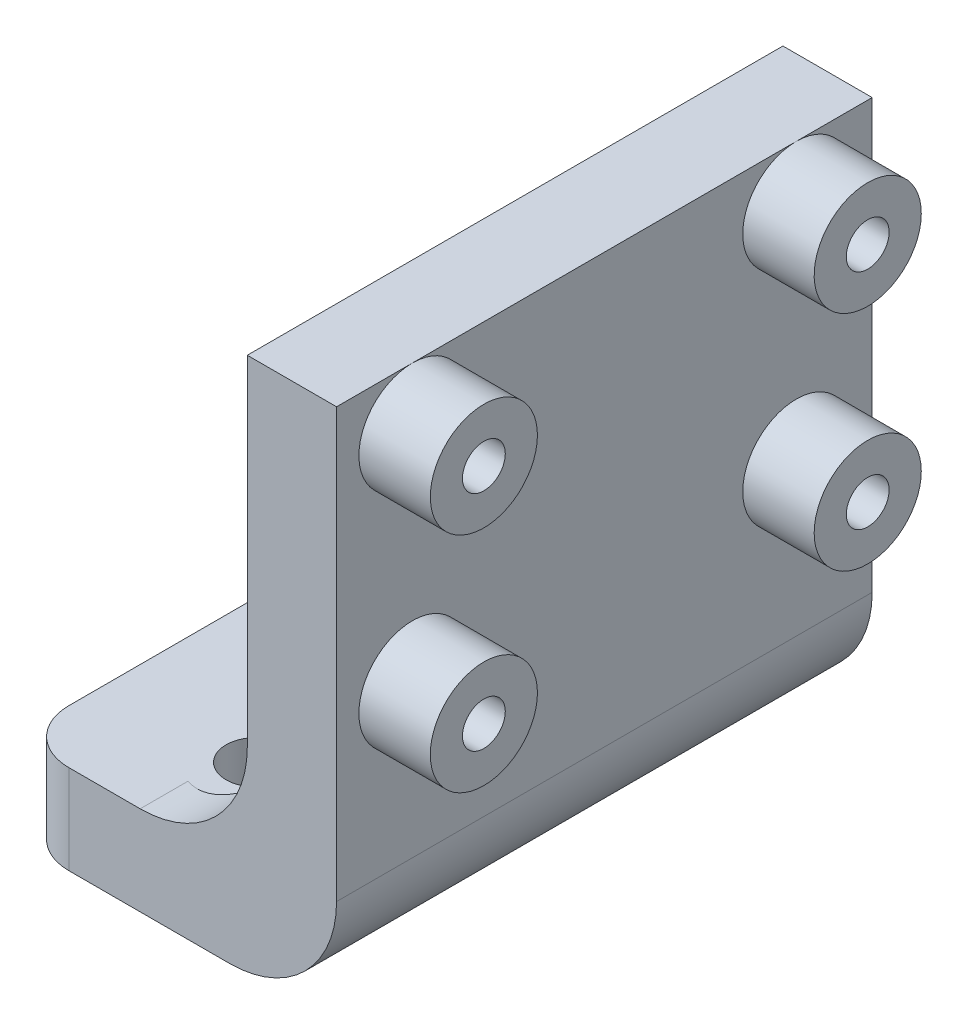
SolidWorks part; units mm, degrees
ref_plane "Front Plane" through (0, 0, 0) normal (0, 0, 1) x (1, 0, 0)
ref_plane "Top Plane" through (0, 0, 0) normal (0, 1, 0) x (1, 0, 0)
ref_plane "Right Plane" through (0, 0, 0) normal (1, 0, 0) x (0, 0, -1)
sketch "Sketch1" plane through (0, 0, 0) normal (0, 1, 0) x (1, 0, 0)
  line L1 (0, 0) -> (18, 0)
  line L2 (0, 0) -> (0, 30)
  line L3 (0, 30) -> (18, 30)
  line L4 (18, 0) -> (18, 30)
  dimension "D1" = 30
  dimension "D2" = 18
extrude "Boss-Extrude1" add sketch "Sketch1" along normal blind 5
sketch "Sketch2" plane through (18, 0, 0) normal (1, 0, 0) x (0, 0, -1)
  line L1 (0, 0) -> (30, 0)
  line L2 (0, 0) -> (0, 30)
  line L3 (0, 30) -> (30, 30)
  line L4 (30, 0) -> (30, 30)
  dimension "D1" = 30
  dimension "D2" = 30
extrude "Boss-Extrude2" add sketch "Sketch2" against normal blind 5
sketch "Sketch3" plane through (18, 0, 0) normal (1, 0, 0) x (0, 0, -1)
  line L0 (15, 30) -> (15, 10.1777) construction
  line L1 (30, 30) -> (0, 30) construction
  line L2 (15, 20.75) -> (28.8198, 20.75) construction
  circle A0 centre (4.25, 27) radius 1.2
  circle A1 centre (25.75, 27) radius 1.2
  circle A2 centre (25.75, 14.5) radius 1.2
  circle A3 centre (4.25, 14.5) radius 1.2
  dimension "D1" = 2.4
  dimension "D2" = 2.4
  dimension "D3" = 21.5
  dimension "D4" = 3
  dimension "D5" = 12.5
extrude "Cut-Extrude1" cut sketch "Sketch3" against normal blind 5
fillet "Fillet1" radius 6 2 edges at (13, 5, -15) (18, 0, -15)
sketch "Sketch4" plane through (18, 0, 0) normal (1, 0, 0) x (0, 0, -1)
  circle A0 centre (25.75, 27) radius 1.2 construction
  circle A1 centre (25.75, 14.5) radius 1.2 construction
  circle A2 centre (4.25, 14.5) radius 1.2 construction
  circle A3 centre (4.25, 27) radius 1.2 construction
  circle A4 centre (25.75, 27) radius 1.2
  circle A5 centre (25.75, 14.5) radius 1.2
  circle A6 centre (4.25, 14.5) radius 1.2
  circle A7 centre (4.25, 27) radius 1.2
  circle A8 centre (4.25, 27) radius 3
  circle A9 centre (25.75, 27) radius 3
  circle A10 centre (4.25, 14.5) radius 3
  circle A11 centre (25.75, 14.5) radius 3
  dimension "D1" = 6
  dimension "D2" = 6
  dimension "D3" = 6
  dimension "D4" = 6
extrude "Boss-Extrude3" add sketch "Sketch4" along normal blind 4
sketch "Sketch5" plane through (0, 0, 0) normal (0, -1, 0) x (1, 0, 0)
  circle A1 centre (8, -25.5101) radius 2.2 construction
  circle A2 centre (8, -5.5101) radius 2.2 construction
  circle A3 centre (8, -25.5101) radius 2.2 construction
  circle A4 centre (8, -5.5101) radius 2.2 construction
  circle A5 centre (8, -5.5101) radius 1.7
  circle A6 centre (8, -25.5101) radius 1.7
  dimension "D1" = 3.4
  dimension "D2" = 3.4
extrude "Cut-Extrude2" cut sketch "Sketch5" against normal blind 24
sketch "Sketch6" plane through (0, 5, 0) normal (0, 1, 0) x (1, 0, 0)
  circle A0 centre (8, 25.5101) radius 1.7 construction
  circle A1 centre (8, 5.5101) radius 1.7 construction
  circle A2 centre (8, 25.5101) radius 1.7 construction
  circle A3 centre (8, 5.5101) radius 1.7 construction
  circle A4 centre (8, 25.5101) radius 3
  circle A5 centre (8, 5.5101) radius 3
  dimension "D1" = 6
  dimension "D2" = 6
extrude "Cut-Extrude3" cut sketch "Sketch6" along normal blind 24
fillet "Fillet2" radius 3 2 edges at (0, 2.5, 0) (0, 2.5, -30)
